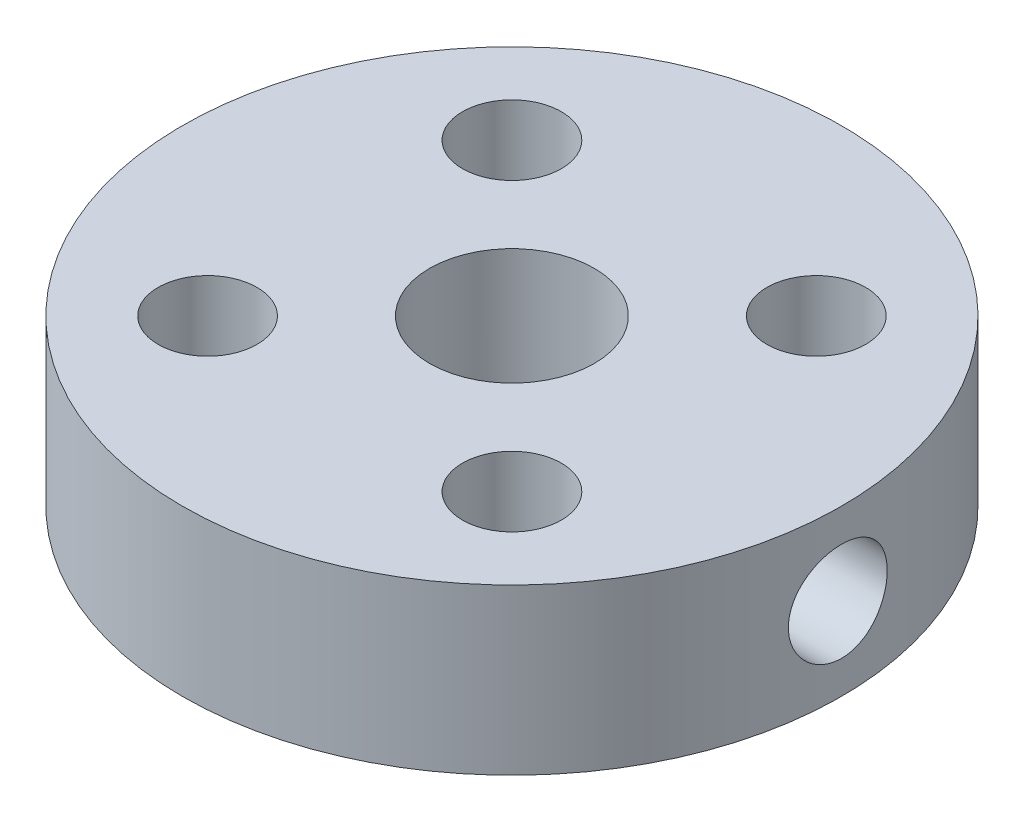
SolidWorks part; units mm, degrees
ref_plane "Спереди" through (0, 0, 0) normal (0, 0, 1) x (1, 0, 0)
ref_plane "Сверху" through (0, 0, 0) normal (0, 1, 0) x (1, 0, 0)
ref_plane "Справа" through (0, 0, 0) normal (1, 0, 0) x (0, 0, -1)
sketch "Эскиз1" plane through (0, 0, 0) normal (0, 1, 0) x (1, 0, 0)
  line L0 (0, 0) -> (0, 10)
  line L1 (0, 0) -> (7.0711, 7.0711)
  circle A0 centre (0, 0) radius 10
  circle A1 centre (0, 0) radius 2
  circle A2 centre (4.6174, 4.6174) radius 1.5
  circle A3 centre (4.6174, -4.6174) radius 1.5
  circle A4 centre (-4.6174, -4.6174) radius 1.5
  circle A5 centre (-4.6174, 4.6174) radius 1.5
  point P17 (0, 0)
  dimension "D1" = 20
  dimension "D3" = 4
  dimension "D5" = 3
  dimension "D2" = 45
  dimension "D4" = 6.53
  dimension "D6" = 4
extrude "Бобышка-Вытянуть1" add sketch "Эскиз1" along normal blind 5 contours A2 L1 A0 L0 A1 | A2 L1 A1 L0 A0 A5 A4 A3
ref_plane "Плоскость1" through (10, 0, 0) normal (1, 0, 0) x (0, 0, -1)
sketch "Эскиз2" plane through (10, 0, 0) normal (1, 0, 0) x (0, 0, -1)
  line L0 (2, 5) -> (-2, 5) construction
  line L1 (10, 0) -> (10, 5) construction
  circle A0 centre (0, 2.5) radius 1.5
  dimension "D2" = 3
  dimension "D1" = 2.5
  dimension "D3" = 10
extrude "Вырез-Вытянуть4" cut sketch "Эскиз2" against normal blind 9
sketch "Sketch1" plane through (0, 0, 0) normal (0, -1, 0) x (1, 0, 0)
  circle A0 centre (0, 0) radius 2.5
  dimension "D1" = 5
extrude "Cut-Extrude1" cut sketch "Sketch1" against normal blind 10
